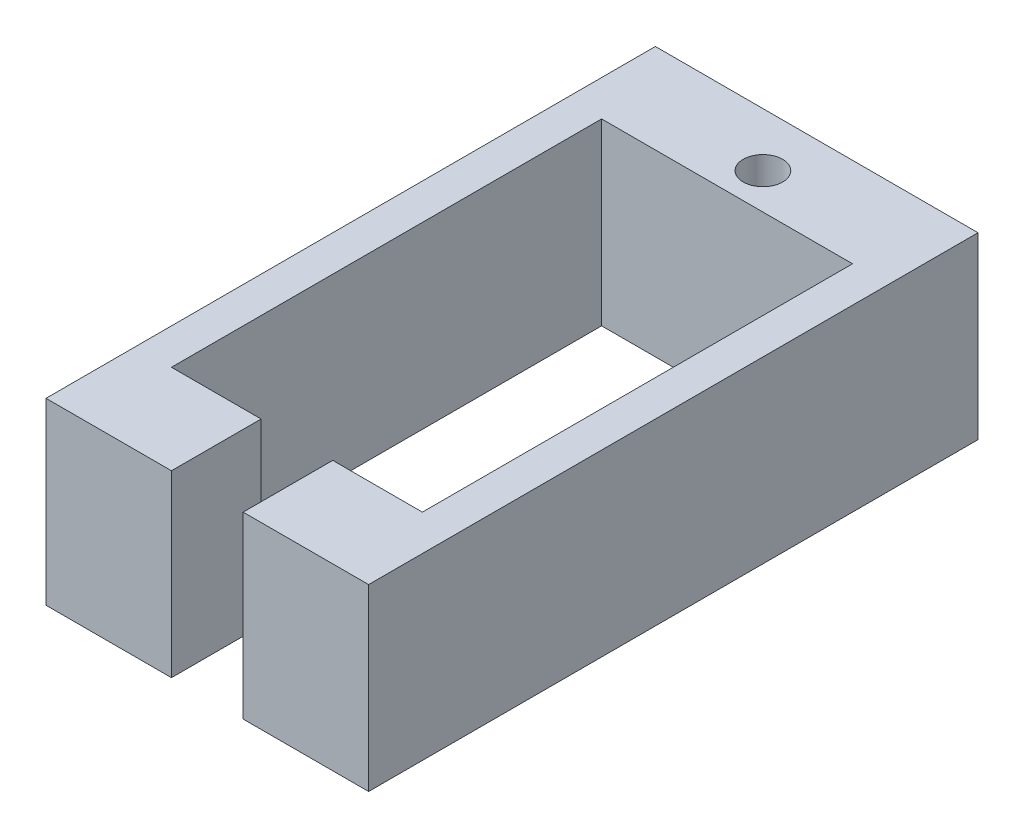
SolidWorks part; units mm, degrees
ref_plane "前视基准面" through (0, 0, 0) normal (0, 0, 1) x (1, 0, 0)
ref_plane "上视基准面" through (0, 0, 0) normal (0, 1, 0) x (1, 0, 0)
ref_plane "右视基准面" through (0, 0, 0) normal (1, 0, 0) x (0, 0, -1)
sketch "草图1" plane through (0, 0, 0) normal (0, 1, 0) x (1, 0, 0)
  line L0 (-7, 12) -> (7, -12) construction
  line L1 (-7, 12) -> (7, 12)
  line L2 (-7, 12) -> (-7, -12)
  line L3 (-7, -12) -> (7, -12)
  line L4 (7, 12) -> (7, -12)
  line L6 (-9, 17) -> (9, 17)
  line L7 (-9, 17) -> (-9, -17)
  line L8 (-9, -17) -> (9, -17)
  line L9 (9, 17) -> (9, -17)
  line L10 (-9, 17) -> (9, -17) construction
  line L11 (-9, -17) -> (9, 17) construction
  point P4 (0, 0)
  dimension "D1" = 2
  dimension "D2" = 5
  dimension "D3" = 14
  dimension "D4" = 24
extrude "凸台-拉伸1" add sketch "草图1" along normal blind 10
sketch "草图2" plane through (0, 0, 0) normal (0, -1, 0) x (1, 0, 0)
  line L0 (0, 14) -> (0, -14) construction
  line L2 (-3.8205, 0) -> (3.7745, 0) construction
  circle A0 centre (0, 14) radius 1.1
  circle A1 centre (0, -14) radius 1.1
  dimension "D2" = 2.2
  dimension "D1" = 28
extrude "切除-拉伸1" cut sketch "草图2" against normal through all
sketch "草图4" plane through (0, 0, 17) normal (0, 0, 1) x (1, 0, 0)
  line L0 (-9, 0) -> (9, 0) construction
  line L1 (-2, 0) -> (2, 0)
  line L2 (-2, 0) -> (-2, 10)
  line L3 (-2, 10) -> (2, 10)
  line L4 (2, 0) -> (2, 10)
  line L5 (-9, 10) -> (9, 10) construction
  dimension "D1" = 4
extrude "切除-拉伸2" cut sketch "草图4" against normal blind 10
